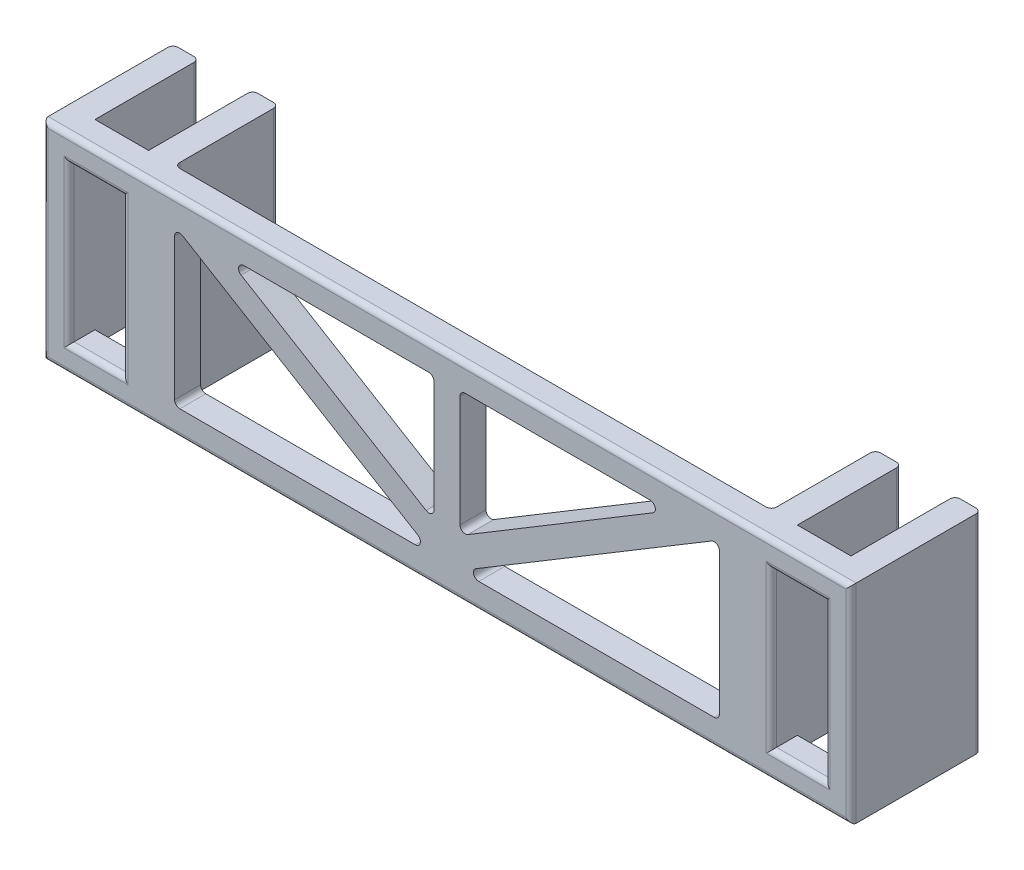
SolidWorks part; units mm, degrees
ref_plane "Front Plane" through (0, 0, 0) normal (0, 0, 1) x (1, 0, 0)
ref_plane "Top Plane" through (0, 0, 0) normal (0, 1, 0) x (1, 0, 0)
ref_plane "Right Plane" through (0, 0, 0) normal (1, 0, 0) x (0, 0, -1)
sketch "Sketch2" plane through (0, 0, 0) normal (0, 1, 0) x (1, 0, 0)
  line L4 (77.65, 10) -> (77.65, -15)
  line L5 (77.65, -15) -> (-77.65, -15)
  line L6 (-77.65, -15) -> (-77.65, 10)
  line L7 (-77.65, 10) -> (-57.35, 10)
  line L8 (-57.35, 10) -> (-57.35, -10)
  line L9 (-57.35, -10) -> (57.35, -10)
  line L10 (57.35, -10) -> (57.35, 10)
  line L11 (57.35, 10) -> (77.65, 10)
  line L13 (72.65, -10) -> (62.35, -10)
  line L14 (72.65, -10) -> (72.65, 10)
  line L15 (72.65, 10) -> (62.35, 10)
  line L16 (62.35, -10) -> (62.35, 10)
  line L17 (-62.35, -10) -> (-72.65, -10)
  line L18 (-62.35, -10) -> (-62.35, 10)
  line L19 (-62.35, 10) -> (-72.65, 10)
  line L20 (-72.65, -10) -> (-72.65, 10)
  line L21 (0, 0) -> (0, -10) construction
  line L27 (0, 0) -> (57.35, 0) construction
  point P18 (0, 0)
  point P20 (0, 0)
  dimension "D2" = 20
  dimension "D3" = 10.3
  dimension "D4" = 10.3
  dimension "D5" = 124.7
  dimension "D8" = 20
  dimension "D9" = 5
  dimension "D10" = 5
  dimension "D11" = 5
  dimension "D12" = 5
  dimension "D13" = 5
  dimension "D14" = 5
extrude "Boss-Extrude2" add sketch "Sketch2" along normal blind 37.5 contours L17 L20 L7 L6 L5 L4 L11 L14 L13 L16 L10 L9 L8 L18
sketch "Sketch3" plane through (0, 0, 0) normal (0, 1, 0) x (1, 0, 0)
  line L0 (77.65, 10) -> (77.65, -15)
  line L1 (77.65, -15) -> (-77.65, -15)
  line L2 (-77.65, -15) -> (-77.65, 10)
  line L3 (-77.65, 10) -> (-75.15, 10)
  line L4 (-77.65, 10) -> (-72.65, 10) construction
  line L5 (-75.15, 10) -> (-75.15, -12.5)
  line L6 (-75.15, -12.5) -> (-59.85, -12.5)
  line L7 (-59.85, -12.5) -> (-59.85, 10)
  line L8 (-62.35, 10) -> (-57.35, 10) construction
  line L9 (-59.85, 10) -> (-57.35, 10)
  line L10 (-57.35, 10) -> (-57.35, -10)
  line L11 (-57.35, -10) -> (57.35, -10)
  line L12 (57.35, -10) -> (57.35, 10)
  line L13 (57.35, 10) -> (59.85, 10)
  line L14 (57.35, 10) -> (62.35, 10) construction
  line L15 (59.85, 10) -> (59.85, -12.5)
  line L16 (59.85, -12.5) -> (75.15, -12.5)
  line L17 (75.15, -12.5) -> (75.15, 10)
  line L18 (72.65, 10) -> (77.65, 10) construction
  line L19 (75.15, 10) -> (77.65, 10)
  line L22 (-62.35, -10) -> (-72.65, -10) construction
  line L23 (72.65, -10) -> (62.35, -10) construction
  dimension "D1" = 2.5
  dimension "D2" = 2.5
extrude "Boss-Extrude3" add sketch "Sketch3" against normal blind 2.5
sketch "Sketch4" plane through (0, 0, 10) normal (0, 0, -1) x (-1, 0, 0)
  line L0 (52.35, 2.5) -> (52.35, 32.5)
  line L1 (52.35, 32.5) -> (2.5, 2.5)
  line L2 (2.5, 2.5) -> (52.35, 2.5)
  line L3 (-2.5, 2.5) -> (-52.35, 2.5)
  line L4 (-52.35, 2.5) -> (-52.35, 32.5)
  line L5 (-52.35, 32.5) -> (-2.5, 2.5)
  line L6 (42.6532, 32.5) -> (2.5, 8.3356)
  line L7 (2.5, 8.3356) -> (2.5, 32.5)
  line L8 (2.5, 32.5) -> (42.6532, 32.5)
  line L9 (-2.5, 8.3356) -> (-2.5, 32.5)
  line L10 (-2.5, 32.5) -> (-42.6532, 32.5)
  line L11 (-42.6532, 32.5) -> (-2.5, 8.3356)
  line L12 (52.35, 2.5) -> (52.35, 32.5) construction
  line L13 (52.35, 32.5) -> (-52.35, 32.5) construction
  line L14 (-52.35, 32.5) -> (-52.35, 2.5) construction
  line L15 (-52.35, 2.5) -> (52.35, 2.5) construction
  line L16 (57.35, 37.5) -> (-57.35, 37.5) construction
  line L17 (57.35, 37.5) -> (57.35, -2.5) construction
  line L18 (-57.35, -2.5) -> (57.35, -2.5) construction
  line L19 (-57.35, 37.5) -> (-57.35, -2.5) construction
  line L20 (2.5, 8.3356) -> (-2.5, 8.3356) construction
  line L21 (0, 0) -> (0, 8.3356) construction
  dimension "D1" = 5
  dimension "D2" = 5
  dimension "D3" = 5
  dimension "D4" = 5
  dimension "D5" = 5
  dimension "D6" = 5
  dimension "D7" = 5
extrude "Cut-Extrude1" cut sketch "Sketch4" against normal through all both and the other way through all
sketch "Sketch8" plane through (0, 0, 10) normal (0, 0, -1) x (-1, 0, 0)
  line L0 (72.65, 37.5) -> (72.65, 0) construction
  line L1 (72.65, 2.5) -> (62.35, 2.5)
  line L2 (72.65, 2.5) -> (72.65, 32.5)
  line L3 (72.65, 32.5) -> (62.35, 32.5)
  line L4 (62.35, 2.5) -> (62.35, 32.5)
  line L5 (62.35, 37.5) -> (62.35, 0) construction
  line L6 (-62.35, 37.5) -> (-62.35, 0) construction
  line L7 (-62.35, 2.5) -> (-72.65, 2.5)
  line L8 (-62.35, 2.5) -> (-62.35, 32.5)
  line L9 (-62.35, 32.5) -> (-72.65, 32.5)
  line L10 (-72.65, 2.5) -> (-72.65, 32.5)
  line L11 (-72.65, 37.5) -> (-72.65, 0) construction
  line L12 (-57.35, -2.5) -> (57.35, -2.5) construction
  line L13 (62.35, 37.5) -> (72.65, 37.5) construction
  dimension "D1" = 5
  dimension "D2" = 5
extrude "Cut-Extrude3" cut sketch "Sketch8" against normal through all
fillet "Fillet1" radius 1 30 edges at (2.5, 8.3356, 12.5) (42.6532, 32.5, 12.5) (2.5, 32.5, 12.5) (-52.35, 2.5, 12.5) (-2.5, 2.5, 12.5) (-52.35, 32.5, 12.5) (-2.5, 32.5, 12.5) (-42.6532, 32.5, 12.5) (-2.5, 8.3356, 12.5) (52.35, 32.5, 12.5) (2.5, 2.5, 12.5) (52.35, 2.5, 12.5) (-72.65, 17.5, 15) (-62.35, 17.5, 15) (62.35, 17.5, 15) (72.65, 17.5, 15) (0, 37.5, 15) (-62.35, 18.75, -10) (-57.35, 17.5, -10) (-57.35, 17.5, 10) (57.35, 17.5, 10) (57.35, 17.5, -10) (62.35, 18.75, -10) (72.65, 18.75, -10) (77.65, 17.5, -10) (77.65, 17.5, 15) (-77.65, 17.5, 15) (-77.65, 17.5, -10) (-72.65, 18.75, -10) (0, -2.5, 15)
